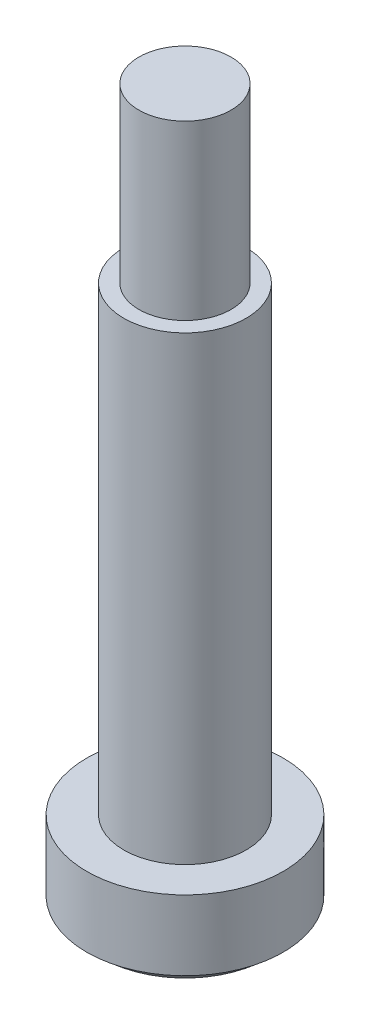
SolidWorks part; units mm, degrees
ref_plane "前视基准面" through (0, 0, 0) normal (0, 0, 1) x (1, 0, 0)
ref_plane "上视基准面" through (0, 0, 0) normal (0, 1, 0) x (1, 0, 0)
ref_plane "右视基准面" through (0, 0, 0) normal (1, 0, 0) x (0, 0, -1)
other "Configuration Table"
sketch "草图1" plane through (0, 0, 0) normal (0, 1, 0) x (1, 0, 0)
  circle A0 centre (0, 0) radius 6.4
  dimension "D1" = 12.8
extrude "凸台-拉伸1" add sketch "草图1" along normal blind 5.4
sketch "草图2" plane through (0, 5.4, 0) normal (0, 1, 0) x (1, 0, 0)
  circle A0 centre (0, 0) radius 3.985
  point P2 (0, 0)
  dimension "D1" = 7.97
extrude "凸台-拉伸2" add sketch "草图2" along normal blind 30
sketch "草图3" plane through (0, 35.4, 0) normal (0, 1, 0) x (1, 0, 0)
  circle A0 centre (0, 0) radius 3
  dimension "D1" = 6
extrude "凸台-拉伸3" add sketch "草图3" along normal blind 11.25
chamfer "倒角1" distance 1 angle 40 1 edges at (0, 0, 6.4)
sketch "草图4" plane through (0, 0, 0) normal (0, -1, 0) x (1, 0, 0)
  line L1 (0, 2.3094) -> (-2, 1.1547)
  line L2 (-2, 1.1547) -> (-2, -1.1547)
  line L3 (-2, -1.1547) -> (0, -2.3094)
  line L4 (0, -2.3094) -> (2, -1.1547)
  line L5 (2, -1.1547) -> (2, 1.1547)
  line L6 (2, 1.1547) -> (0, 2.3094)
  circle A0 centre (0, 0) radius 2 construction
  point P1 (-2, 1.1923)
  point P10 (0, 0)
  dimension "D1" = 4
extrude "切除-拉伸1" cut sketch "草图4" against normal blind 3
